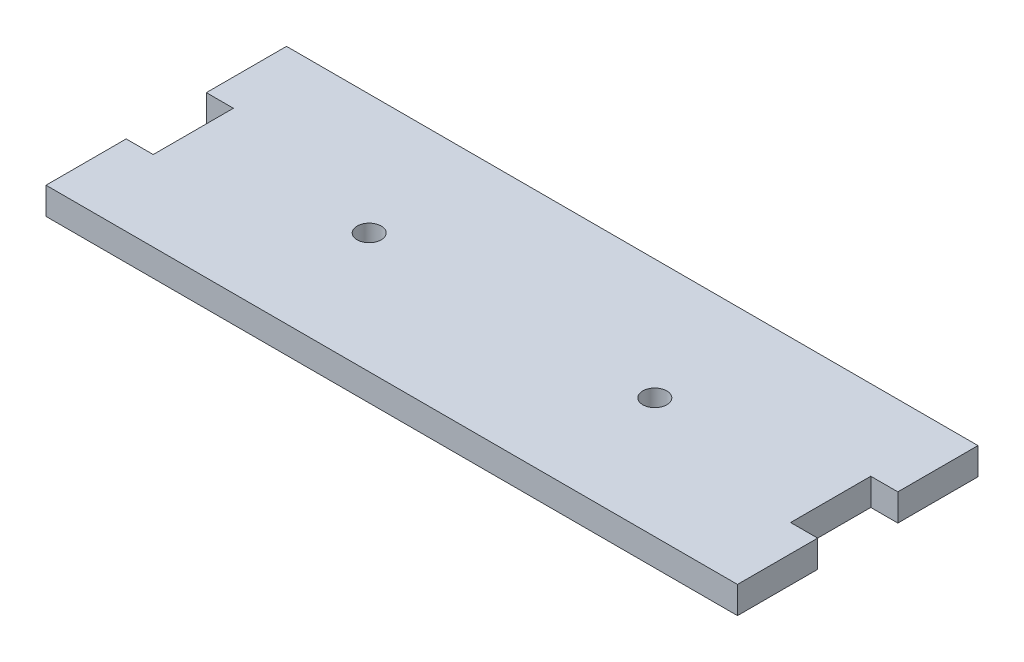
SolidWorks part; units mm, degrees
ref_plane "Front Plane" through (0, 0, 0) normal (0, 0, 1) x (1, 0, 0)
ref_plane "Top Plane" through (0, 0, 0) normal (0, 1, 0) x (1, 0, 0)
ref_plane "Right Plane" through (0, 0, 0) normal (1, 0, 0) x (0, 0, -1)
sketch "Sketch1" plane through (0, 0, 0) normal (0, 1, 0) x (1, 0, 0)
  line L0 (115, 80) -> (115, 0) construction
  line L1 (0, 0) -> (230, 0)
  line L2 (0, 0) -> (0, 80)
  line L3 (0, 80) -> (230, 80)
  line L4 (230, 0) -> (230, 80)
  line L5 (0, 40) -> (230, 40) construction
  line L6 (8.8542, 80) -> (8.8542, 53.3333) construction
  line L7 (9, 80) -> (0, 80)
  line L8 (9, 80) -> (9, 0)
  line L9 (9, 0) -> (0, 0)
  line L10 (0, 80) -> (0, 0)
  line L11 (8.8542, 53.3333) -> (8.8542, 26.6667) construction
  line L12 (0, 53.3333) -> (9, 53.3333)
  line L13 (0, 53.3333) -> (0, 26.6667)
  line L14 (0, 26.6667) -> (9, 26.6667)
  line L15 (9, 53.3333) -> (9, 26.6667)
  line L16 (8.8542, 26.6667) -> (8.8542, 0) construction
  line L17 (221.1458, 26.6667) -> (221.1458, 0) construction
  line L18 (221.1458, 53.3333) -> (221.1458, 26.6667) construction
  line L19 (221.1458, 80) -> (221.1458, 53.3333) construction
  line L20 (221, 53.3333) -> (221, 26.6667)
  line L21 (230, 26.6667) -> (221, 26.6667)
  line L22 (230, 53.3333) -> (230, 26.6667)
  line L23 (230, 53.3333) -> (221, 53.3333)
  line L24 (230, 80) -> (230, 0)
  line L25 (221, 0) -> (230, 0)
  line L26 (221, 80) -> (221, 0)
  line L27 (221, 80) -> (230, 80)
  line L28 (230, 0) -> (230, 80)
  circle A0 centre (67.5, 40) radius 4
  circle A1 centre (162.5, 40) radius 4
  dimension "D4" = 8
  dimension "D1" = 230
  dimension "D2" = 80
  dimension "D3" = 9
  dimension "D5" = 47.5
extrude "Boss-Extrude1" add sketch "Sketch1" along normal blind 9 contours L26 L3 L8 L1 L20 A0 A1 | L10 L12 L8 L3 | L14 L2 L1 L8 | L3 L26 L23 L4 | L21 L26 L1 L4
equation "\"D5@Sketch1\"=95/2"
